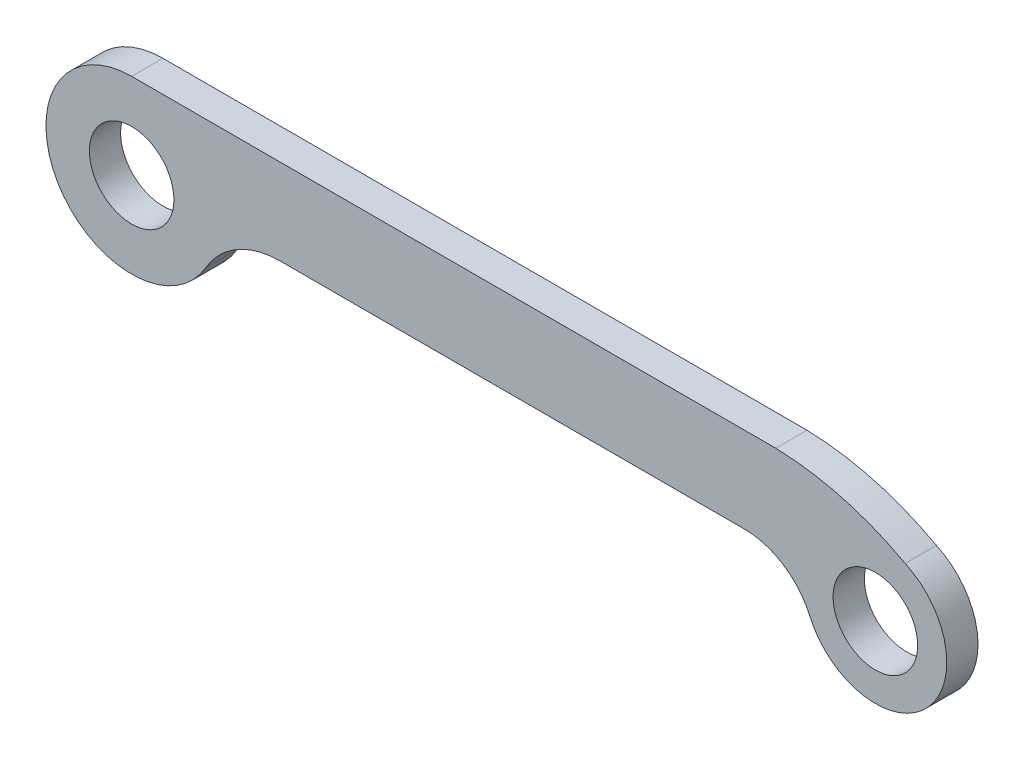
SolidWorks part; units mm, degrees
ref_plane "Front Plane" through (0, 0, 0) normal (0, 0, 1) x (1, 0, 0)
ref_plane "Top Plane" through (0, 0, 0) normal (0, 1, 0) x (1, 0, 0)
ref_plane "Right Plane" through (0, 0, 0) normal (1, 0, 0) x (0, 0, -1)
sketch "Sketch2" plane through (0, 0, 0) normal (0, 0, 1) x (1, 0, 0)
  line L0 (0, 19.2) -> (144.3392, 19.2)
  line L1 (33.2554, 0) -> (137.3163, 0)
  circle A0 centre (0, 0) radius 9.472
  circle A1 centre (0, 0) radius 19.2
  circle A2 centre (166.6445, -3.1994) radius 9.472
  circle A3 centre (166.6445, -3.1994) radius 16
  arc A5 (144.3392, 19.2) -> (173.3287, 11.3375) centre (142.5328, -44.8343) cw
  arc A6 (137.3163, 0) -> (151.9804, -9.5997) centre (137.3163, -16) cw
  arc A7 (33.2554, 0) -> (16.6277, -9.6) centre (33.2554, -19.2) ccw
  dimension "D1" = 18.944
  dimension "D2" = 38.4
  dimension "D3" = 32
  dimension "D4" = 64.0598
  dimension "D5" = 16.6277
  dimension "D6" = 137.3163
  dimension "D7" = 142.5328
  dimension "D8" = 144.3392
  dimension "D9" = 151.9804
  dimension "D10" = 166.6445
extrude "Boss-Extrude1" add sketch "Sketch2" along normal blind 7 contours A7 L1 A6 A3 A5 L0 A1 | A1 A0 | A3 A2
